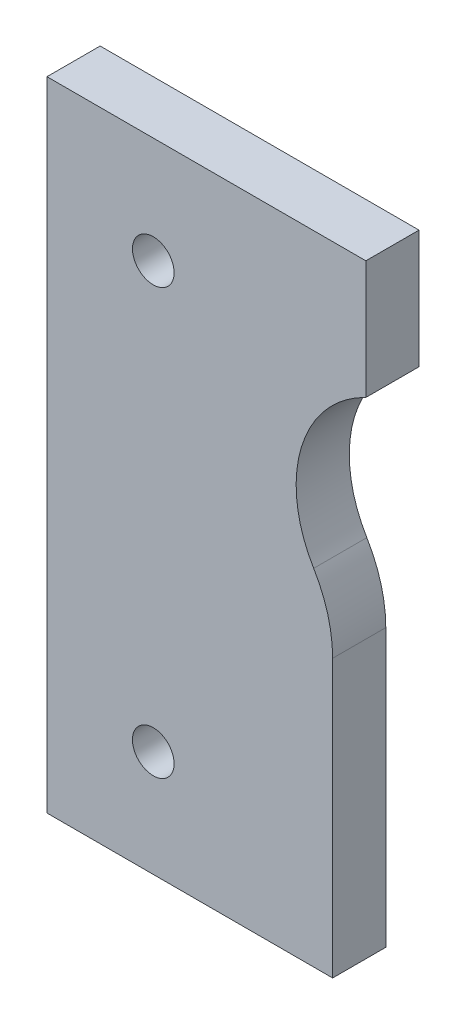
SolidWorks part; units mm, degrees
material "6061 Alloy"
ref_plane "X-Y Datum" through (0, 0, 0) normal (0, 0, 1) x (1, 0, 0)
ref_plane "X-Z Datum" through (0, 0, 0) normal (0, 1, 0) x (1, 0, 0)
ref_plane "Y-Z Datum" through (0, 0, 0) normal (1, 0, 0) x (0, 0, -1)
sketch "Sketch1" plane through (0, 0, 0) normal (0, 0, 1) x (1, 0, 0)
  line L0 (-6.35, 27.3812) -> (-44.45, 27.3812)
  line L6 (-10.3187, -15.7343) -> (-10.3187, -48.8188)
  line L10 (-44.45, 27.3812) -> (-44.45, -48.8188)
  line L11 (-44.45, -48.8188) -> (-10.3187, -48.8188)
  line L12 (-6.35, 27.3812) -> (-6.35, 13.2369)
  arc A7 (-10.3187, -15.7343) -> (-12.5852, -7.5598) centre (-26.1937, -15.7343) ccw
  arc A9 (-6.35, 13.2369) -> (-12.5852, -7.5598) centre (0, 0) ccw
  circle A12 centre (-31.75, 14.6812) radius 2.4892
  circle A13 centre (-31.75, -36.1188) radius 2.4892
  point P5 (-10.3187, -48.8188)
  point P11 (-6.35, 13.2369)
  dimension "D1" = 15.875
  dimension "D4" = 6.35
  dimension "D8" = 12.7
  dimension "D10" = 38.1
  dimension "D2" = 14.6812
  dimension "D7" = 4.9784
  dimension "D3" = 14.1443
  dimension "D5" = 10.3187
  dimension "D9" = 76.2
  dimension "D11" = 12.7
  dimension "D12" = 12.7
extrude "Boss-Extrude1" add sketch "Sketch1" along normal mid plane 6.35
